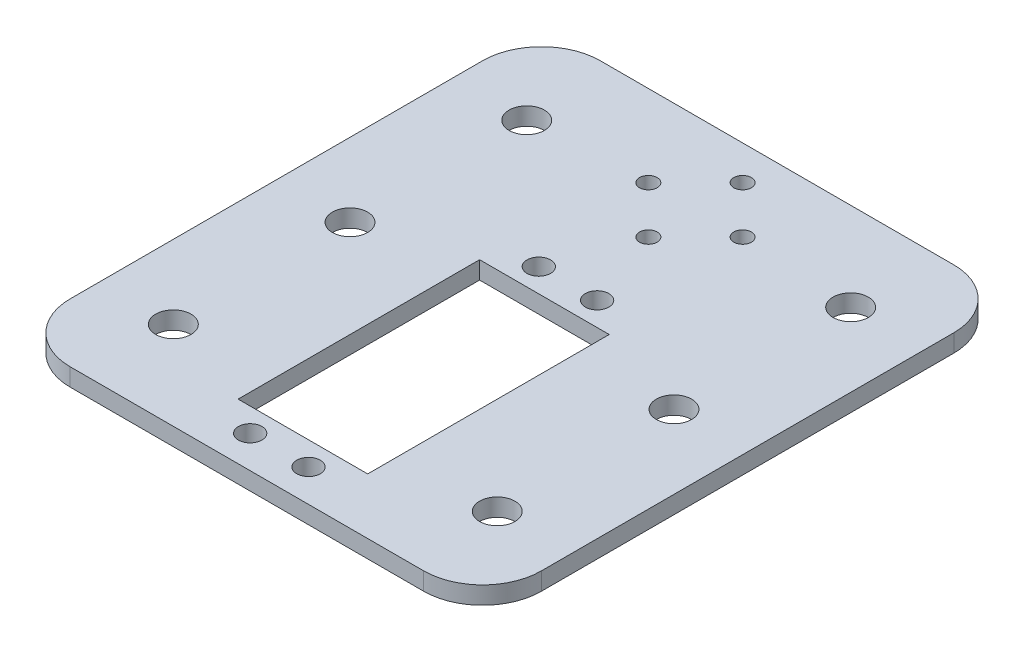
SolidWorks part; units mm, degrees
material "C-玻璃纤维"
ref_plane "前视基准面" through (0, 0, 0) normal (0, 0, 1) x (1, 0, 0)
ref_plane "上视基准面" through (0, 0, 0) normal (0, 1, 0) x (1, 0, 0)
ref_plane "右视基准面" through (0, 0, 0) normal (1, 0, 0) x (0, 0, -1)
other "Configuration Table"
sketch "草图1" plane through (0, 0, 0) normal (0, 1, 0) x (1, 0, 0)
  line L0 (10, 50.306) -> (10, -41.9644) construction
  line L1 (-40, -30) -> (40, -30)
  line L2 (-40, -30) -> (-40, 60)
  line L4 (40, -30) -> (40, 60)
  line L5 (0, 30) -> (0, -30) construction
  line L6 (-40, 0) -> (40, 0) construction
  line L7 (-10, 50.306) -> (-10, -41.9644) construction
  line L8 (-40, 60) -> (40, 60)
  line L13 (-11, -20.5) -> (11, -20.5)
  line L14 (-11, -20.5) -> (-11, 20.5)
  line L15 (-11, 20.5) -> (11, 20.5)
  line L16 (11, -20.5) -> (11, 20.5)
  line L17 (0, 20.5) -> (0, -20.5) construction
  line L18 (-11, 0) -> (11, 0) construction
  line L19 (-27.5, 15) -> (-27.5, 45) construction
  circle A0 centre (27.5, 15) radius 3
  circle A1 centre (27.5, -15) radius 3
  circle A2 centre (-27.5, -15) radius 3
  circle A3 centre (-27.5, 15) radius 3
  circle A6 centre (4.95, 24.5) radius 2
  circle A7 centre (-4.95, 24.5) radius 2
  circle A8 centre (4.95, -24.5) radius 2
  circle A9 centre (-4.95, -24.5) radius 2
  circle A10 centre (-27.5, 45) radius 3
  circle A11 centre (27.5, 45) radius 3
  point P24 (0, 0)
  dimension "D4" = 6
  dimension "D7" = 80
  dimension "D9" = 12.5
  dimension "D3" = 4
  dimension "D2" = 30
  dimension "D5" = 49
  dimension "D6" = 30
  dimension "D8" = 9.9
  dimension "D10" = 41
  dimension "D11" = 60
  dimension "D13" = 30
  dimension "D14" = 20
  dimension "D15" = 22
  dimension "D12" = 2
extrude "凸台-拉伸1" add sketch "草图1" along normal blind 3
fillet "圆角1" radius 10 4 edges at (-40, 1.5, -60) (40, 1.5, -60) (40, 1.5, 30) (-40, 1.5, 30)
sketch "草图2" plane through (0, 0, 0) normal (0, 1, 0) x (1, 0, 0)
  line L5 (-34.4048, 46.15) -> (39.1378, 46.15) construction
  line L6 (0, 87.7765) -> (0, -51.5351) construction
  circle A1 centre (0, 46.15) radius 8 construction
  circle A2 centre (0, 54.15) radius 1.5
  circle A3 centre (8, 46.15) radius 1.5
  circle A4 centre (0, 38.15) radius 1.5
  circle A5 centre (-8, 46.15) radius 1.5
  point P24 (0, 46.15)
  dimension "D4" = 16
  dimension "D5" = 3
  dimension "D1" = 46.15
  dimension "D6" = 4
extrude "切除-拉伸1" cut sketch "草图2" along normal through all
